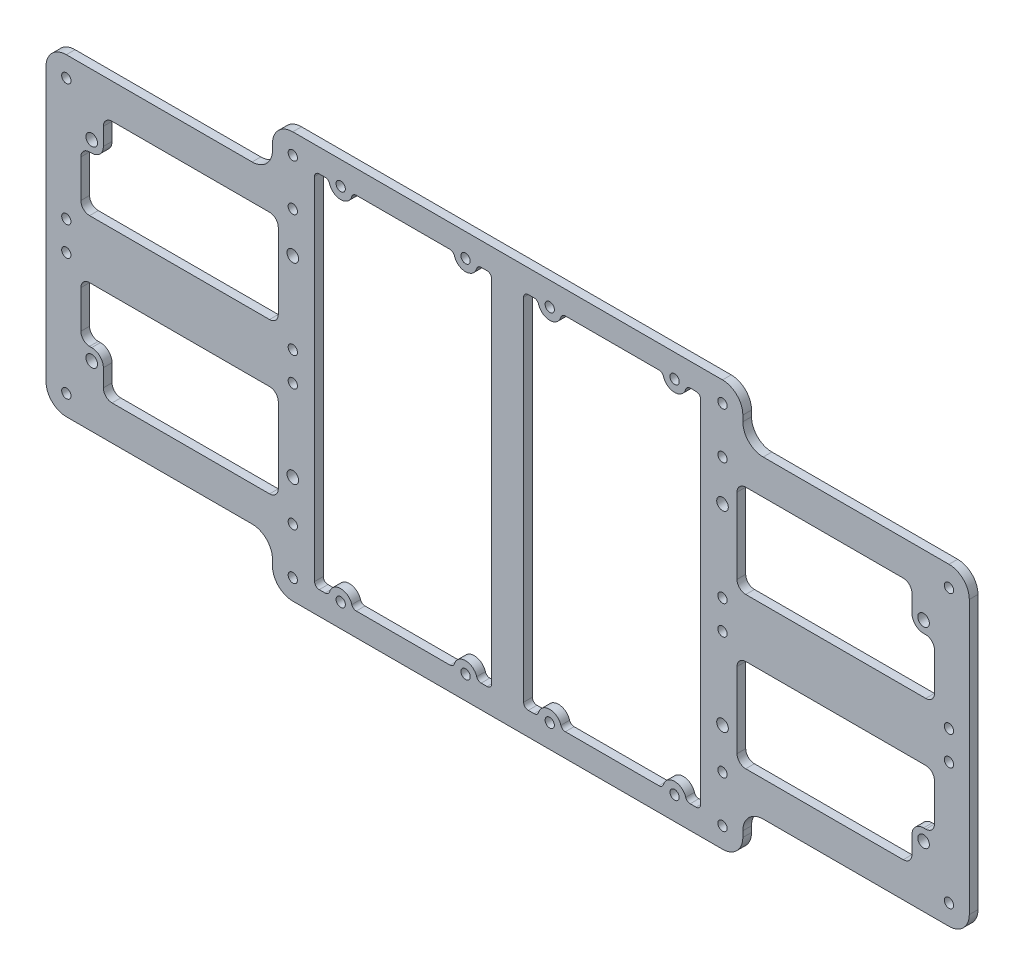
SolidWorks part; units mm, degrees
material "Thornel Mat VMA"
ref_plane "Front Plane" through (0, 0, 0) normal (0, 0, 1) x (1, 0, 0)
ref_plane "Top Plane" through (0, 0, 0) normal (0, 1, 0) x (1, 0, 0)
ref_plane "Right Plane" through (0, 0, 0) normal (1, 0, 0) x (0, 0, -1)
sketch "Model" plane through (0, 0, 0) normal (0, 0, 1) x (1, 0, 0)
  line L0 (-62.8666, 62) -> (-64.9, 62)
  line L1 (-66.5, 60.4) -> (-66.5, -60.4)
  line L2 (-64.9, -62) -> (-62.8666, -62)
  line L3 (-52.1334, 62) -> (-19.8666, 62)
  line L4 (-9.1334, 62) -> (-7.1, 62)
  line L5 (-5.5, 60.4) -> (-5.5, -60.4)
  line L6 (-7.1, -62) -> (-9.1334, -62)
  line L7 (-52.1334, -62) -> (-19.8666, -62)
  line L8 (9.1334, 62) -> (7.1, 62)
  line L9 (5.5, 60.4) -> (5.5, -60.4)
  line L10 (7.1, -62) -> (9.1334, -62)
  line L11 (19.8666, 62) -> (52.1334, 62)
  line L12 (62.8666, 62) -> (64.9, 62)
  line L13 (66.5, 60.4) -> (66.5, -60.4)
  line L14 (64.9, -62) -> (62.8666, -62)
  line L15 (19.8666, -62) -> (52.1334, -62)
  line L16 (-159, -47) -> (-159, 47)
  line L17 (-74, 70) -> (74, 70)
  line L18 (-136.25, -42) -> (-82, -42)
  line L19 (-79, -39) -> (-79, -13)
  line L20 (-82, -10) -> (-144, -10)
  line L21 (-147, -13) -> (-147, -26)
  line L22 (-136.25, 42) -> (-82, 42)
  line L23 (-79, 39) -> (-79, 13)
  line L24 (-82, 10) -> (-144, 10)
  line L25 (-147, 13) -> (-147, 26)
  line L26 (136.25, -42) -> (82, -42)
  line L27 (79, -39) -> (79, -13)
  line L28 (82, -10) -> (144, -10)
  line L29 (147, -13) -> (147, -26)
  line L30 (136.25, 42) -> (82, 42)
  line L31 (82, 10) -> (144, 10)
  line L32 (79, 39) -> (79, 13)
  line L33 (147, 13) -> (147, 26)
  line L34 (-81, 61) -> (-81, 63)
  line L35 (159, -47) -> (159, 47)
  line L36 (-152, 54) -> (-88, 54)
  line L37 (-152, -54) -> (-88, -54)
  line L38 (152, 54) -> (88, 54)
  line L39 (152, -54) -> (88, -54)
  line L40 (-139.25, 33) -> (-139.25, 39)
  line L41 (-143.25, 29) -> (-144, 29)
  line L42 (-139.25, -33) -> (-139.25, -39)
  line L43 (-143.25, -29) -> (-144, -29)
  line L44 (139.25, 33) -> (139.25, 39)
  line L45 (143.25, 29) -> (144, 29)
  line L46 (139.25, -33) -> (139.25, -39)
  line L47 (143.25, -29) -> (144, -29)
  line L48 (81, 61) -> (81, 63)
  line L49 (-74, -70) -> (74, -70)
  line L50 (-81, -61) -> (-81, -63)
  line L51 (81, -61) -> (81, -63)
  circle A0 centre (-57.5, 62) radius 1.6
  circle A1 centre (-14.5, 62) radius 1.6
  circle A2 centre (-57.5, -62) radius 1.6
  circle A3 centre (-14.5, -62) radius 1.6
  arc A4 (-61.3333, 60.8571) -> (-53.6667, 60.8571) centre (-57.5, 62) ccw
  arc A5 (-52.1334, 62) -> (-53.6667, 60.8571) centre (-52.1334, 60.4) ccw
  arc A6 (-61.3333, 60.8571) -> (-62.8666, 62) centre (-62.8666, 60.4) ccw
  arc A7 (-18.3333, 60.8571) -> (-10.6667, 60.8571) centre (-14.5, 62) ccw
  arc A8 (-9.1334, 62) -> (-10.6667, 60.8571) centre (-9.1334, 60.4) ccw
  arc A9 (-18.3333, 60.8571) -> (-19.8666, 62) centre (-19.8666, 60.4) ccw
  arc A10 (-53.6667, -60.8571) -> (-61.3333, -60.8571) centre (-57.5, -62) ccw
  arc A11 (-53.6667, -60.8571) -> (-52.1334, -62) centre (-52.1334, -60.4) ccw
  arc A12 (-62.8666, -62) -> (-61.3333, -60.8571) centre (-62.8666, -60.4) ccw
  arc A13 (-10.6667, -60.8571) -> (-18.3333, -60.8571) centre (-14.5, -62) ccw
  arc A14 (-10.6667, -60.8571) -> (-9.1334, -62) centre (-9.1334, -60.4) ccw
  arc A15 (-19.8666, -62) -> (-18.3333, -60.8571) centre (-19.8666, -60.4) ccw
  arc A16 (-66.5, -60.4) -> (-64.9, -62) centre (-64.9, -60.4) ccw
  arc A17 (-64.9, 62) -> (-66.5, 60.4) centre (-64.9, 60.4) ccw
  arc A18 (-7.1, -62) -> (-5.5, -60.4) centre (-7.1, -60.4) ccw
  arc A19 (-5.5, 60.4) -> (-7.1, 62) centre (-7.1, 60.4) ccw
  circle A20 centre (14.5, 62) radius 1.6
  circle A21 centre (57.5, 62) radius 1.6
  circle A22 centre (14.5, -62) radius 1.6
  circle A23 centre (57.5, -62) radius 1.6
  arc A24 (10.6667, 60.8571) -> (18.3333, 60.8571) centre (14.5, 62) ccw
  arc A25 (19.8666, 62) -> (18.3333, 60.8571) centre (19.8666, 60.4) ccw
  arc A26 (10.6667, 60.8571) -> (9.1334, 62) centre (9.1334, 60.4) ccw
  arc A27 (53.6667, 60.8571) -> (61.3333, 60.8571) centre (57.5, 62) ccw
  arc A28 (62.8666, 62) -> (61.3333, 60.8571) centre (62.8666, 60.4) ccw
  arc A29 (53.6667, 60.8571) -> (52.1334, 62) centre (52.1334, 60.4) ccw
  arc A30 (18.3333, -60.8571) -> (10.6667, -60.8571) centre (14.5, -62) ccw
  arc A31 (18.3333, -60.8571) -> (19.8666, -62) centre (19.8666, -60.4) ccw
  arc A32 (9.1334, -62) -> (10.6667, -60.8571) centre (9.1334, -60.4) ccw
  arc A33 (61.3333, -60.8571) -> (53.6667, -60.8571) centre (57.5, -62) ccw
  arc A34 (61.3333, -60.8571) -> (62.8666, -62) centre (62.8666, -60.4) ccw
  arc A35 (52.1334, -62) -> (53.6667, -60.8571) centre (52.1334, -60.4) ccw
  arc A36 (5.5, -60.4) -> (7.1, -62) centre (7.1, -60.4) ccw
  arc A37 (7.1, 62) -> (5.5, 60.4) centre (7.1, 60.4) ccw
  arc A38 (64.9, -62) -> (66.5, -60.4) centre (64.9, -60.4) ccw
  arc A39 (66.5, 60.4) -> (64.9, 62) centre (64.9, 60.4) ccw
  arc A40 (-82, -42) -> (-79, -39) centre (-82, -39) ccw
  arc A41 (-79, -13) -> (-82, -10) centre (-82, -13) ccw
  arc A42 (-144, -10) -> (-147, -13) centre (-144, -13) ccw
  circle A43 centre (-152, -47) radius 1.6
  circle A44 centre (-152, -5) radius 1.6
  circle A45 centre (-74, -47) radius 1.6
  circle A46 centre (-74, -5) radius 1.6
  arc A47 (-136.25, 42) -> (-139.25, 39) centre (-136.25, 39) ccw
  arc A48 (-79, 39) -> (-82, 42) centre (-82, 39) ccw
  arc A49 (-82, 10) -> (-79, 13) centre (-82, 13) ccw
  arc A50 (-144, 29) -> (-147, 26) centre (-144, 26) ccw
  arc A51 (-147, 13) -> (-144, 10) centre (-144, 13) ccw
  circle A52 centre (-152, 47) radius 1.6
  circle A53 centre (-152, 5) radius 1.6
  circle A54 centre (-74, 47) radius 1.6
  circle A55 centre (-74, 5) radius 1.6
  arc A56 (79, -39) -> (82, -42) centre (82, -39) ccw
  arc A57 (82, -10) -> (79, -13) centre (82, -13) ccw
  arc A58 (147, -13) -> (144, -10) centre (144, -13) ccw
  circle A59 centre (152, -47) radius 1.6
  circle A60 centre (152, -5) radius 1.6
  circle A61 centre (74, -47) radius 1.6
  circle A62 centre (74, -5) radius 1.6
  circle A63 centre (74, 5) radius 1.6
  arc A64 (82, 42) -> (79, 39) centre (82, 39) ccw
  arc A65 (144, 10) -> (147, 13) centre (144, 13) ccw
  arc A66 (79, 13) -> (82, 10) centre (82, 13) ccw
  circle A67 centre (152, 47) radius 1.6
  circle A68 centre (152, 5) radius 1.6
  circle A69 centre (74, 47) radius 1.6
  arc A70 (-152, 54) -> (-159, 47) centre (-152, 47) ccw
  arc A71 (-74, 70) -> (-81, 63) centre (-74, 63) ccw
  arc A72 (-88, 54) -> (-81, 61) centre (-88, 61) ccw
  arc A73 (-159, -47) -> (-152, -54) centre (-152, -47) ccw
  arc A74 (159, 47) -> (152, 54) centre (152, 47) ccw
  arc A75 (152, -54) -> (159, -47) centre (152, -47) ccw
  circle A76 centre (-74, 33) radius 2
  circle A77 centre (-74, -33) radius 2
  circle A78 centre (74, 33) radius 2
  circle A79 centre (74, -33) radius 2
  circle A80 centre (-143.25, 33) radius 2
  arc A81 (-143.25, 29) -> (-139.25, 33) centre (-143.25, 33) ccw
  arc A82 (-139.25, -39) -> (-136.25, -42) centre (-136.25, -39) ccw
  arc A83 (-147, -26) -> (-144, -29) centre (-144, -26) ccw
  circle A84 centre (-143.25, -33) radius 2
  arc A85 (-139.25, -33) -> (-143.25, -29) centre (-143.25, -33) ccw
  arc A86 (139.25, 39) -> (136.25, 42) centre (136.25, 39) ccw
  arc A87 (147, 26) -> (144, 29) centre (144, 26) ccw
  circle A88 centre (143.25, 33) radius 2
  arc A89 (139.25, 33) -> (143.25, 29) centre (143.25, 33) ccw
  arc A90 (136.25, -42) -> (139.25, -39) centre (136.25, -39) ccw
  arc A91 (144, -29) -> (147, -26) centre (144, -26) ccw
  circle A92 centre (143.25, -33) radius 2
  arc A93 (143.25, -29) -> (139.25, -33) centre (143.25, -33) ccw
  circle A94 centre (-74, 63) radius 1.6
  arc A95 (81, 63) -> (74, 70) centre (74, 63) ccw
  arc A96 (81, 61) -> (88, 54) centre (88, 61) ccw
  circle A97 centre (74, 63) radius 1.6
  arc A98 (-81, -63) -> (-74, -70) centre (-74, -63) ccw
  arc A99 (-81, -61) -> (-88, -54) centre (-88, -61) ccw
  circle A100 centre (-74, -63) radius 1.6
  arc A101 (74, -70) -> (81, -63) centre (74, -63) ccw
  arc A102 (88, -54) -> (81, -61) centre (88, -61) ccw
  circle A103 centre (74, -63) radius 1.6
extrude "Boss-Extrude1" add sketch "Model" along normal blind 3
